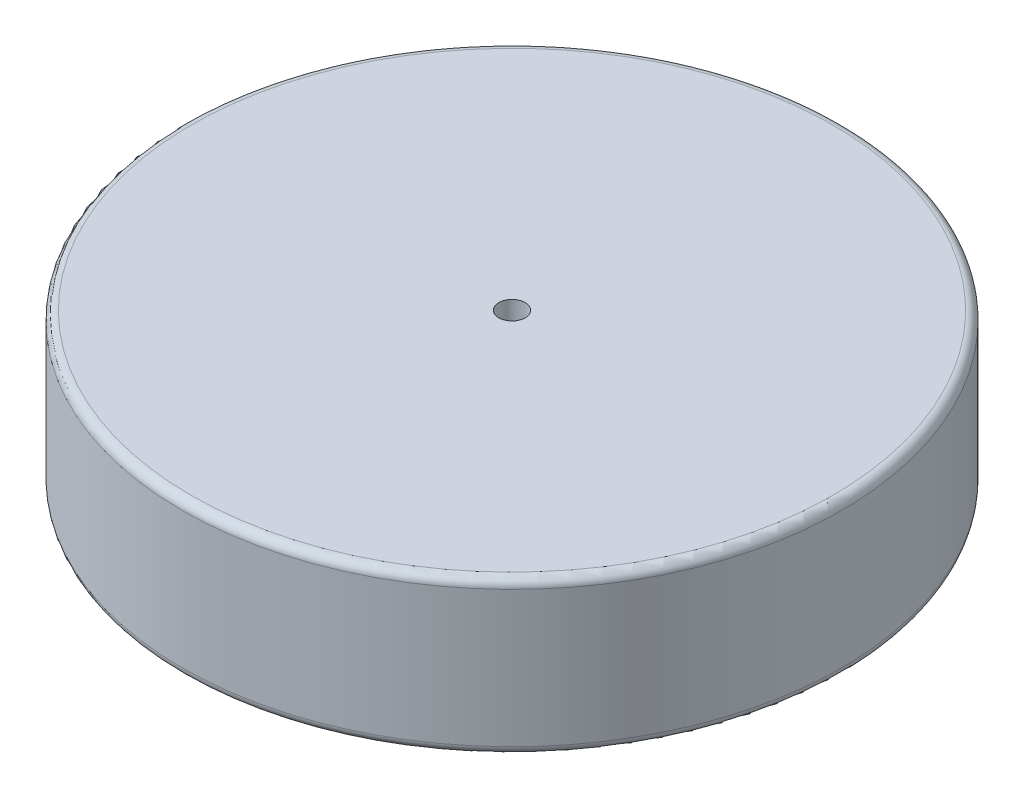
SolidWorks part; units mm, degrees
ref_plane "Front Plane" through (0, 0, 0) normal (0, 0, 1) x (1, 0, 0)
ref_plane "Top Plane" through (0, 0, 0) normal (0, 1, 0) x (1, 0, 0)
ref_plane "Right Plane" through (0, 0, 0) normal (1, 0, 0) x (0, 0, -1)
sketch "Sketch1" plane through (0, 0, 0) normal (0, 1, 0) x (1, 0, 0)
  circle A0 centre (0, 0) radius 75
  circle A1 centre (0, 0) radius 3
  dimension "D1" = 150
  dimension "D2" = 6
extrude "Boss-Extrude1" add sketch "Sketch1" along normal blind 35
fillet "Fillet1" radius 2 2 edges at (0, 35, 75) (0, 0, 75)
